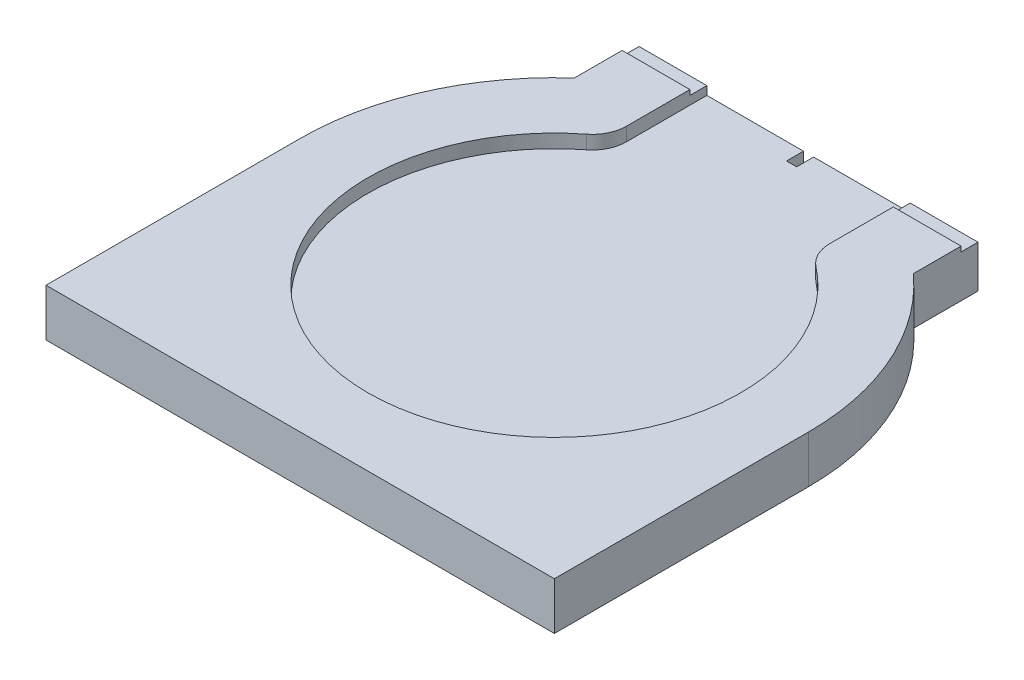
SolidWorks part; units mm, degrees
ref_plane "Front Plane" through (0, 0, 0) normal (0, 0, 1) x (1, 0, 0)
ref_plane "Top Plane" through (0, 0, 0) normal (0, 1, 0) x (1, 0, 0)
ref_plane "Right Plane" through (0, 0, 0) normal (1, 0, 0) x (0, 0, -1)
sketch "Sketch1" plane through (0, 0, 0) normal (0, 1, 0) x (1, 0, 0)
  line L0 (-5, 7.5) -> (-5, 5.5902)
  line L2 (-3, 5.5) -> (-3, 5.1235)
  line L4 (3, 5.5) -> (3, 5.1235)
  line L5 (5, 7.5) -> (5, 5.5902)
  line L6 (-5, 7.5) -> (-3, 7.5)
  line L7 (-3, 5.5) -> (-3, 7.5)
  line L8 (3, 5.5) -> (3, 7.5)
  line L9 (3, 7.5) -> (5, 7.5)
  line L10 (-5, 7.5) -> (5, 7.5) construction
  line L11 (-3, 5.5) -> (3, 5.5) construction
  line L12 (-7.5, 0) -> (-7.5, -7.5)
  line L13 (-7.5, -7.5) -> (7.5, -7.5)
  line L14 (7.5, -7.5) -> (7.5, 0)
  arc A0 (-3.3846, 4.3352) -> (3.3846, 4.3352) centre (0, 0) ccw
  arc A1 (-3.3846, 4.3352) -> (-3, 5.1235) centre (-4, 5.1235) ccw
  arc A2 (3.3846, 4.3352) -> (3, 5.1235) centre (4, 5.1235) cw
  arc A3 (-5, 5.5902) -> (-5, 5.5902) centre (-5, 5.5902) ccw
  arc A4 (-5, 5.5902) -> (-7.5, 0) centre (0, 0) ccw
  arc A5 (5, 5.5902) -> (5, 5.5902) centre (5, 5.5902) cw
  arc A6 (7.5, 0) -> (5, 5.5902) centre (0, 0) ccw
  arc A7 (-5, 5.5902) -> (5, 5.5902) centre (0, 0) ccw construction
  point P19 (-7.5, 0)
  point P22 (7.5, 0)
  point P23 (0, -7.5)
  dimension "D1" = 11
  dimension "D4" = 1
  dimension "D6" = 1
  dimension "D2" = 6
  dimension "D3" = 3
  dimension "D5" = 7.5
  dimension "D7" = 2
extrude "Boss-Extrude1" add sketch "Sketch1" along normal blind 0.8
sketch "Sketch2" plane through (0, 0.8, 0) normal (0, 1, 0) x (1, 0, 0)
  line L0 (5, 5.5902) -> (5, 7.5) construction
  line L1 (5, 7.5) -> (3, 7.5) construction
  line L2 (-5, 7.5) -> (-5, 5.5902) construction
  line L3 (-3, 7.5) -> (-5, 7.5) construction
  line L4 (5, 5.5902) -> (5, 7.5)
  line L5 (5, 7.5) -> (3, 7.5)
  line L6 (-5, 7.5) -> (-5, 5.5902)
  line L7 (-3, 7.5) -> (-5, 7.5)
  line L8 (-3, 7.5) -> (3, 7.5)
  line L9 (7.5, -7.5) -> (7.5, 0) construction
  line L10 (-7.5, -7.5) -> (7.5, -7.5) construction
  line L11 (-7.5, 0) -> (-7.5, -7.5) construction
  line L12 (7.5, -7.5) -> (7.5, 0)
  line L13 (-7.5, -7.5) -> (7.5, -7.5)
  line L14 (-7.5, 0) -> (-7.5, -7.5)
  arc A2 (7.5, 0) -> (5, 5.5902) centre (0, 0) ccw construction
  arc A3 (-5, 5.5902) -> (-7.5, 0) centre (0, 0) ccw construction
  arc A4 (7.5, 0) -> (5, 5.5902) centre (0, 0) ccw
  arc A5 (-5, 5.5902) -> (-7.5, 0) centre (0, 0) ccw
extrude "Boss-Extrude2" add sketch "Sketch2" along normal blind 1
sketch "Sketch3" plane through (0, 0, 0) normal (0, -1, 0) x (1, 0, 0)
  line L0 (-3, -7.5) -> (-5, -7.5) construction
  line L1 (5, -7.5) -> (3, -7.5) construction
  line L2 (5, -5.5902) -> (5, -7.5) construction
  line L3 (-5, -7.5) -> (-5, -5.5902) construction
  line L4 (-3, -7.5) -> (-5, -7.5)
  line L5 (5, -7.5) -> (3, -7.5)
  line L6 (5, -5.5902) -> (5, -7.5)
  line L7 (-5, -7.5) -> (-5, -5.5902)
  line L8 (-3, -7.5) -> (3, -7.5)
  line L9 (-7.5, 0) -> (-7.5, 7.5) construction
  line L10 (-7.5, 7.5) -> (7.5, 7.5) construction
  line L11 (7.5, 7.5) -> (7.5, 0) construction
  line L12 (-7.5, 0) -> (-7.5, 7.5)
  line L13 (-7.5, 7.5) -> (7.5, 7.5)
  line L14 (7.5, 7.5) -> (7.5, 0)
  arc A2 (-7.5, 0) -> (-5, -5.5902) centre (0, 0) ccw construction
  arc A3 (5, -5.5902) -> (7.5, 0) centre (0, 0) ccw construction
  arc A4 (-7.5, 0) -> (-5, -5.5902) centre (0, 0) ccw
  arc A5 (5, -5.5902) -> (7.5, 0) centre (0, 0) ccw
extrude "Boss-Extrude3" add sketch "Sketch3" along normal blind 1
sketch "Sketch4" plane through (0, 0, -7.5) normal (0, 0, -1) x (-1, 0, 0)
  line L0 (-5, 1.8) -> (-5, -1) construction
  line L3 (-5, 1.8) -> (-5, -1) construction
  line L4 (-5, 0.55) -> (-0.15, 0.55)
  line L5 (-5, 0.55) -> (-5, 0.25)
  line L6 (-5, 0.25) -> (-0.15, 0.25)
  line L7 (5, 0.55) -> (5, 0.25)
  line L8 (5, 1.8) -> (5, -1) construction
  line L9 (-3, 0.8) -> (3, 0.8) construction
  line L10 (-5, 1.8) -> (5, 1.8) construction
  line L11 (-0.15, 1.8) -> (0.15, 1.8)
  line L12 (-0.15, 1.8) -> (-0.15, 0.55)
  line L13 (-0.15, -1) -> (0.15, -1)
  line L14 (0.15, 1.8) -> (0.15, 0.55)
  line L15 (5, -1) -> (-5, -1) construction
  line L16 (0.15, 0.55) -> (5, 0.55)
  line L17 (0.15, 0.25) -> (5, 0.25)
  line L18 (0.15, 0.25) -> (0.15, -1)
  line L19 (-0.15, 0.25) -> (-0.15, -1)
  point P0 (-5, 0.4)
  point P1 (0, 0.8)
  dimension "D1" = 0.3
  dimension "D2" = 0.15
  dimension "D3" = 0.3
  dimension "D4" = 0.15
extrude "Cut-Extrude1" cut sketch "Sketch4" against normal blind 0.5
ref_plane "Plane1" through (0, 0.4, 0) normal (0, -1, 0) x (-1, 0, 0)
sketch "Sketch5" plane through (0, 0.4, 0) normal (0, -1, 0) x (-1, 0, 0)
  line L1 (-11.791, 9.9486) -> (10.4809, 9.9486)
  line L2 (-11.791, 9.9486) -> (-11.791, -10.2489)
  line L3 (-11.791, -10.2489) -> (10.4809, -10.2489)
  line L4 (10.4809, 9.9486) -> (10.4809, -10.2489)
extrude "Cut-Extrude2" cut sketch "Sketch5" against normal blind 3
